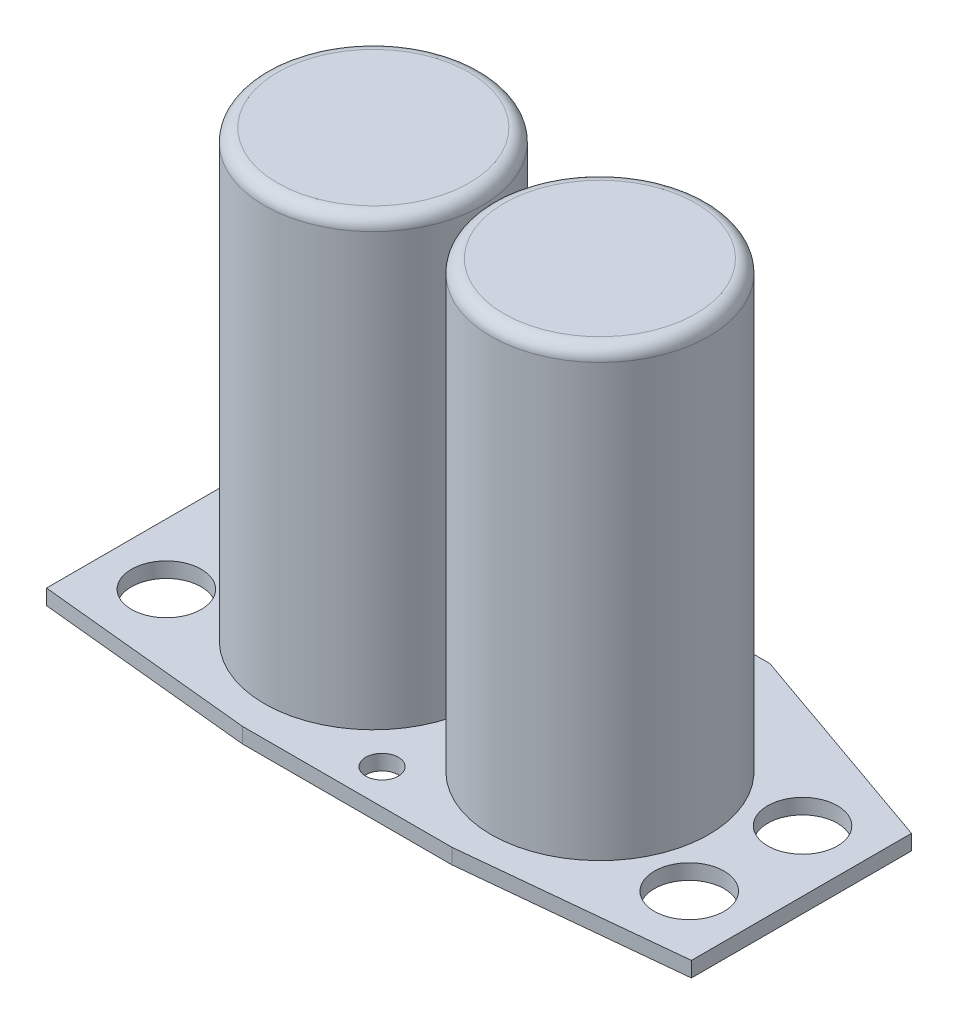
SolidWorks part; units mm, degrees
ref_plane "Front Plane" through (0, 0, 0) normal (0, 0, 1) x (1, 0, 0)
ref_plane "Top Plane" through (0, 0, 0) normal (0, 1, 0) x (1, 0, 0)
ref_plane "Right Plane" through (0, 0, 0) normal (1, 0, 0) x (0, 0, -1)
sketch "Sketch1" plane through (0, 0, 0) normal (0, 1, 0) x (1, 0, 0)
  line L0 (18.796, 18.542) -> (18.796, 0) construction
  line L1 (0, 0) -> (37.592, 0)
  line L2 (0, 0) -> (0, 18.542)
  line L3 (0, 18.542) -> (37.592, 18.542)
  line L4 (37.592, 0) -> (37.592, 18.542)
  line L5 (0, 14.097) -> (12.7, 18.542)
  line L6 (0, 1.27) -> (12.7, 0)
  line L7 (37.592, 14.097) -> (24.892, 18.542)
  line L8 (37.592, 1.27) -> (24.892, 0)
  circle A0 centre (13.208, 16.51) radius 0.9525
  circle A1 centre (24.384, 16.51) radius 0.9525
  circle A2 centre (18.796, 2.032) radius 0.9525
  dimension "D4" = 1.905
  dimension "D5" = 2.032
  dimension "D10" = 2.032
  dimension "D1" = 18.542
  dimension "D2" = 37.592
  dimension "D3" = 5.588
  dimension "D6" = 4.445
  dimension "D7" = 12.7
  dimension "D8" = 1.27
  dimension "D9" = 12.7
extrude "Boss-Extrude1" add sketch "Sketch1" along normal blind 0.889 contours L0 L3 L5 L2 L6 L1 A2 A0 | L3 L0 A2 L1 L8 L4 L7 A1
sketch "Sketch2" plane through (0, 0.889, 0) normal (0, 1, 0) x (1, 0, 0)
  line L0 (18.796, 18.542) -> (18.796, 0) construction
  line L1 (12.7, 18.542) -> (24.892, 18.542) construction
  line L2 (12.7, 0) -> (24.892, 0) construction
  line L3 (0, 1.27) -> (0, 14.097) construction
  circle A1 centre (3.556, 11.303) radius 2.032
  circle A2 centre (3.556, 4.699) radius 2.032
  circle A4 centre (34.036, 4.699) radius 2.032
  circle A5 centre (34.036, 11.303) radius 2.032
  dimension "D4" = 4.064
  dimension "D5" = 4.064
  dimension "D7" = 6.604
  dimension "D3" = 3.556
  dimension "D6" = 4.699
sketch "Sketch3" plane through (0, 0.889, 0) normal (0, 1, 0) x (1, 0, 0)
  circle A0 centre (12.192, 8.128) radius 6.35
  circle A1 centre (25.4, 8.128) radius 6.35
  dimension "D1" = 12.7
extrude "Boss-Extrude2" add sketch "Sketch3" along normal blind 25.908
extrude "Cut-Extrude1" cut sketch "Sketch2" against normal through all
fillet "Fillet1" radius 0.762 2 edges at (25.4, 26.797, -1.778) (12.192, 26.797, -1.778)
